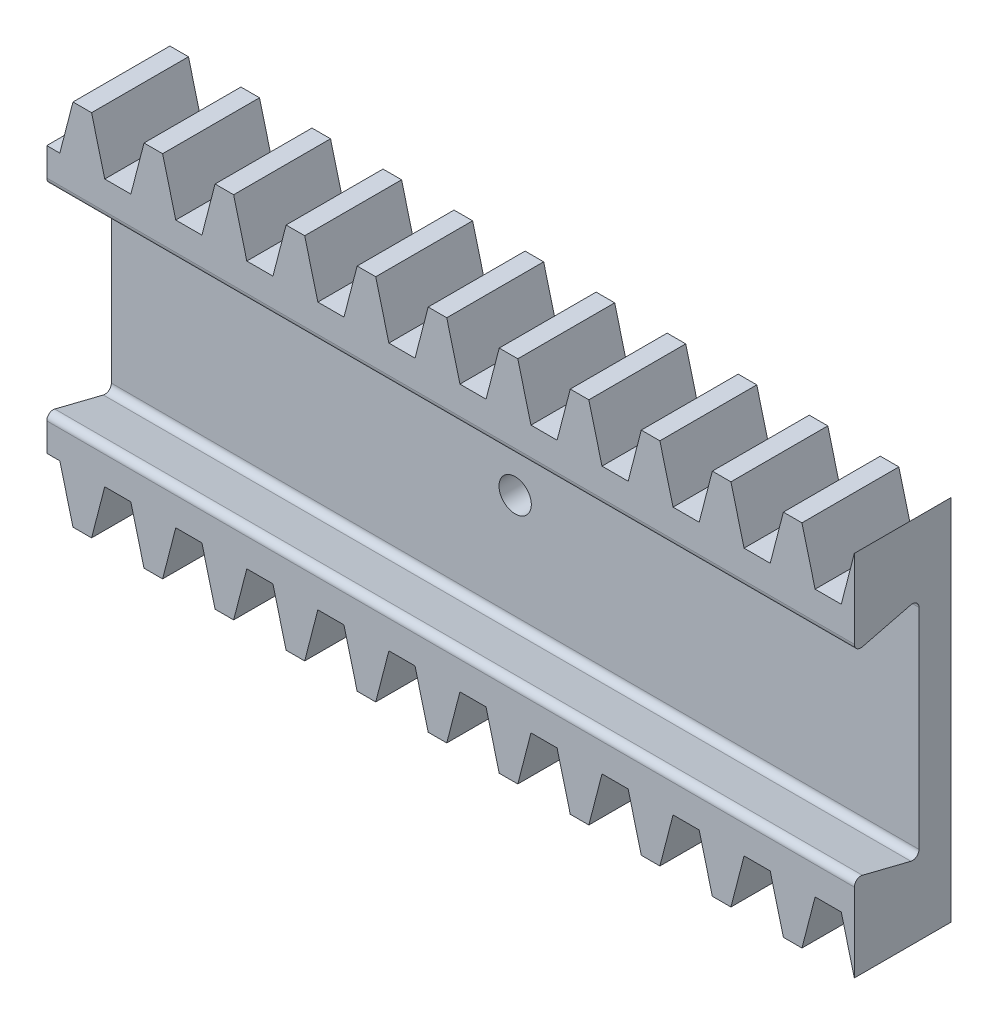
SolidWorks part; units mm, degrees
extrude "Blank" add sketch "BlankSke" against normal blind 3
sketch "BlankSke" plane through (0, 0, 0) normal (0, 0, 1) x (1, 0, 0)
  line L1 (0, 0) -> (25, 0)
  line L2 (0, 0) -> (0, 5.7)
  line L3 (0, 5.7) -> (25, 5.7)
  line L4 (25, 0) -> (25, 5.7)
  dimension "Length" = 25
  dimension "Blank_height" = 5.7
ref_plane "Plane1" through (0, 0, 0) normal (0, 0, 1) x (1, 0, 0)
ref_plane "Plane2" through (0, 0, 0) normal (0, 1, 0) x (1, 0, 0)
ref_plane "Plane3" through (0, 0, 0) normal (1, 0, 0) x (0, 0, -1)
other "Configuration Table"
sketch "HoldingSke" plane through (0, 0, 0) normal (0, 1, 0) x (1, 0, 0)
  line L0 (0, 0) -> (0.1988, 1.4147)
  line L1 (-15, 0) -> (100, 0) construction
  line L2 (0, 0) -> (-2.1039, 2.3779)
  line L3 (0, 0) -> (-11.863, 4.5341)
  line L4 (0, 0) -> (8.4147, 1.9427)
  line L5 (0, 0) -> (-23.7986, -8.8762)
  line L6 (0, 0) -> (-10.5278, -7.1032)
  line L9 (-67.7845, 28.3722) -> (-43.5808, 34.6317)
  line L10 (-76.2, 3.0779) -> (-71.2, 3.0779)
  line L11 (0, 0) -> (-3, 0)
  line L12 (-76.2, 101.6) -> (-76.173, 101.6)
  line L13 (24.9733, 27.94) -> (52.9518, 28.4284)
  line L14 (24.9733, 27.94) -> (24.9743, 27.94)
  line L15 (24.9733, 27.94) -> (100.4006, 29.5858)
  circle A0 centre (0, 0) radius 19.05
  circle A1 centre (0, 0) radius 2.5
  circle A2 centre (0, 0) radius 12.7
  dimension "MPH" = 5
  dimension "Diameter" = 38.1
  dimension "Num_teeth" = 13
  dimension "Pitch" = 1.4286
  dimension "Show_teeth" = 998
  dimension "Thickness" = 12.7
  dimension "Ap" = 14.5
  dimension "Pitch_height" = 5
  dimension "Width" = 3
  dimension "Backlash" = 0.027
  dimension "Addendum_fac" = 1
  dimension "Dedendum_fac" = 1.25
  dimension "Clearance_fac" = 0.25
  dimension "Dedendum_add" = 0.001
  dimension "Length" = 25
  dimension "Module" = 0.7
sketch "TooCutSkeIll" plane through (0, 0, 0) normal (0, 0, 1) x (1, 0, 0)
  line L0 (-0.8064, 5.679) -> (-0.4386, 4.2569)
  line L1 (-0.2682, 4.125) -> (0.2682, 4.125)
  line L2 (0.4386, 4.2569) -> (0.8064, 5.679)
  line L3 (25, 5.7) -> (0, 5.7) construction
  line L4 (0, 0) -> (0, 64.897) construction
  line L5 (-13.208, 5) -> (12.954, 5) construction
  line L6 (0, 0) -> (25, 0) construction
  line L7 (0.6308, 5) -> (0.6308, 48.7463) construction
  line L8 (-0.6308, 5) -> (-0.6308, 48.7463) construction
  line L9 (0.8335, 5.7) -> (0.8335, 5.7254)
  line L10 (-0.8335, 5.7) -> (-0.8335, 5.7254)
  line L11 (-0.8335, 5.7254) -> (0.8335, 5.7254)
  arc A0 (0.2682, 4.125) -> (0.4386, 4.2569) centre (0.2682, 4.301) ccw
  arc A1 (-0.4386, 4.2569) -> (-0.2682, 4.125) centre (-0.2682, 4.301) ccw
  arc A2 (0.8335, 5.7) -> (0.8064, 5.679) centre (0.8335, 5.672) ccw
  arc A3 (-0.8064, 5.679) -> (-0.8335, 5.7) centre (-0.8335, 5.672) ccw
  dimension "Pitch_height" = 5
  dimension "Addendum_plus" = 0.7254
  dimension "Pressure_angle" = 14.5
  dimension "Gap_width" = 1.2616
  dimension "Dedendum" = 0.875
extrude "ToothCutIll" [suppressed] cut sketch "TooCutSkeIll" against normal through all
sketch "TooCutSkeSim" plane through (0, 0, 0) normal (0, 0, 1) x (1, 0, 0)
  line L0 (0.4045, 4.125) -> (-0.4045, 4.125)
  line L1 (0.8184, 5.7254) -> (0.4045, 4.125)
  line L2 (0, 17.4625) -> (0, 53.467) construction
  line L3 (0.8184, 5.7254) -> (-0.8184, 5.7254)
  line L6 (-0.8184, 5.7254) -> (-0.4045, 4.125)
  line L9 (-0.6308, 5) -> (0.6308, 5) construction
  line L10 (0, 0) -> (25, 0) construction
  line L11 (0.6308, 5) -> (0.6308, 53.467) construction
  line L12 (-0.6308, 5) -> (-0.6308, 53.467) construction
  dimension "Pitch_height" = 5
  dimension "Addendum_plus" = 0.7254
  dimension "Pressure_angle" = 14.5
  dimension "Gap_width" = 1.2616
  dimension "Dedendum" = 0.875
extrude "ToothCutSim" cut sketch "TooCutSkeSim" against normal through all
pattern_linear "TeethCuts" count 12 spacing 2.1991 along (1, 0, 0) of "ToothCutIll", "ToothCutSim"
mirror "镜向1" [suppressed]
mirror "镜向2" about plane through (0, 0, -3) normal (0, -1, 0) of "Blank", "ToothCutSim", "TeethCuts"
sketch "草图1" plane through (0, 0, 0) normal (-1, 0, 0) x (0, 0, 1)
  line L1 (0, 4.125) -> (0, -4.125) construction
  line L4 (-3, 0) -> (0, 0) construction
  line L5 (-3, 4.125) -> (-3, -4.125) construction
  line L7 (0, -3) -> (0, 3)
  line L8 (0, 3) -> (-2, 3.5)
  line L9 (-2, 3.5) -> (-2, -3.5)
  line L10 (0, -3) -> (-2, -3.5)
  point P11 (-2.5, 0)
  point P12 (-2, 0)
  dimension "D1" = 3
  dimension "D2" = 3.5
  dimension "D3" = 2
extrude "切除-拉伸2" cut sketch "草图1" against normal through all
fillet "圆角1" radius 0.2 1 edges at (12.5, -3.5, -2)
fillet "圆角2" radius 0.2 1 edges at (12.5, 3.5, -2)
fillet "圆角3" radius 0.2 2 edges at (12.5, -3, 0) (12.5, 3, 0)
sketch "草图2" plane through (0, 0, -3) normal (0, 0, -1) x (-1, 0, 0)
  line L0 (0, 0) -> (-25, 0) construction
  line L1 (0, 4.125) -> (0, -4.125) construction
  line L2 (-25, -5.692) -> (-25, 5.692) construction
  circle A0 centre (-12.5, 0) radius 1.5
  dimension "D1" = 3
extrude "凸台-拉伸1" add sketch "草图2" along normal blind 1.5
sketch "草图3" plane through (0, 0, -4.5) normal (0, 0, -1) x (-1, 0, 0)
  circle A0 centre (-12.5, 0) radius 0.5
  dimension "D1" = 1
extrude "切除-拉伸3" cut sketch "草图3" against normal through all
equation "' \"Module@HoldingSke\" = 6.35"
equation "' \"Num_teeth@HoldingSke\" = 12"
equation "' \"Ap@HoldingSke\" =  20"
equation "' \"Ap@HoldingSke\" = 20"
equation "' \"Width@HoldingSke\" = 0.25 * 25.4"
equation "' \"Show_teeth@HoldingSke\" = 500"
equation "' \"Backlash@HoldingSke\" = 0.009 * 25.4"
equation "' \"Addendum_fac@HoldingSke\" = 1.0"
equation "' \"Dedendum_fac@HoldingSke\" = 1.25"
equation "' \"Dedendum_add@HoldingSke\" = 0.00005 * 25.4"
equation "' \"Clearance_fac@HoldingSke\" = 0.25"
equation "' \"Pitch_height@HoldingSke\" = 1 * 25.4"
equation "' \"Length@HoldingSke\" = 4.71 * 25.4"
equation "\"Pitch@HoldingSke\" = 1 / \"Module@HoldingSke\""
equation "\"MPH@HoldingSke\" = \"Dedendum_fac@HoldingSke\" / \"Pitch@HoldingSke\" + 2 * \"Dedendum_add@HoldingSke\" + 0.002 * 25.4"
equation "\"MPH@HoldingSke\" = ((sgn( \"MPH@HoldingSke\" - \"Pitch_height@HoldingSke\")+1)*( \"MPH@HoldingSke\" - \"Pitch_height@HoldingSke\"))/2 + \"Pitch_height@HoldingSke\""
equation "\"Blank_height@BlankSke\" = \"Pitch_height@HoldingSke\" + \"Addendum_fac@HoldingSke\"  / \"Pitch@HoldingSke\" "
equation "\"Length@BlankSke\" =  \"Length@HoldingSke\""
equation "\"Face_width@Blank\" = \"Width@HoldingSke\""
equation "\"Pressure_angle@TooCutSkeIll\" = \"Ap@HoldingSke\""
equation "\"Addendum_plus@TooCutSkeIll\" =  \"Addendum_fac@HoldingSke\"  / \"Pitch@HoldingSke\" + 0.001 *25.4"
equation "\"Dedendum@TooCutSkeIll\" = \"Dedendum_fac@HoldingSke\"  / \"Pitch@HoldingSke\""
equation "\"Pitch_height@TooCutSkeIll\" =  \"MPH@HoldingSke\""
equation "\"Gap_width@TooCutSkeIll\" = 3.14159265 / 2 / \"Pitch@HoldingSke\" + 6 * \"Backlash@HoldingSke\""
equation "\"Pressure_angle@TooCutSkeSim\" = \"Ap@HoldingSke\""
equation "\"Addendum_plus@TooCutSkeSim\" =  \"Addendum_fac@HoldingSke\"  / \"Pitch@HoldingSke\" + 0.001 * 25.4"
equation "\"Dedendum@TooCutSkeSim\" = \"Dedendum_fac@HoldingSke\"  / \"Pitch@HoldingSke\""
equation "\"Pitch_height@TooCutSkeSim\" =  \"MPH@HoldingSke\""
equation "\"Gap_width@TooCutSkeSim\" = 3.14159265 / 2 / \"Pitch@HoldingSke\" + 6 * \"Backlash@HoldingSke\""
equation "\"Root_fillet@TooCutSkeIll\" = \"Clearance_fac@HoldingSke\" / \"Pitch@HoldingSke\" + \"Dedendum_add@HoldingSke\""
equation "\"Break_rad@TooCutSkeIll\" = 0.02 / \"Pitch@HoldingSke\" * 2"
equation "\"Linear_pitch@TeethCuts\" = 3.14159265 / \"Pitch@HoldingSke\""
equation "\"Num_teeth@HoldingSke\" = int( ( \"Length@HoldingSke\" + 0 ) / (3.14159265 / \"Pitch@HoldingSke\")) + 0.9999  + 1"
equation " \"Num_teeth@TeethCuts\" = int( \"Show_teeth@HoldingSke\" ) + 1"
equation " \"Num_teeth@TeethCuts\" = ((sgn( \"Num_teeth@TeethCuts\" - \"Num_teeth@HoldingSke\" )-1)*( \"Num_teeth@TeethCuts\" - \"Num_teeth@HoldingSke\" ))/-2+ \"Num_teeth@HoldingSke\""
equation " \"Num_teeth@TeethCuts\" = ((sgn( \"Num_teeth@TeethCuts\" - 2.0)+1)*( \"Num_teeth@TeethCuts\" - 2.0))/2 +2.0"
